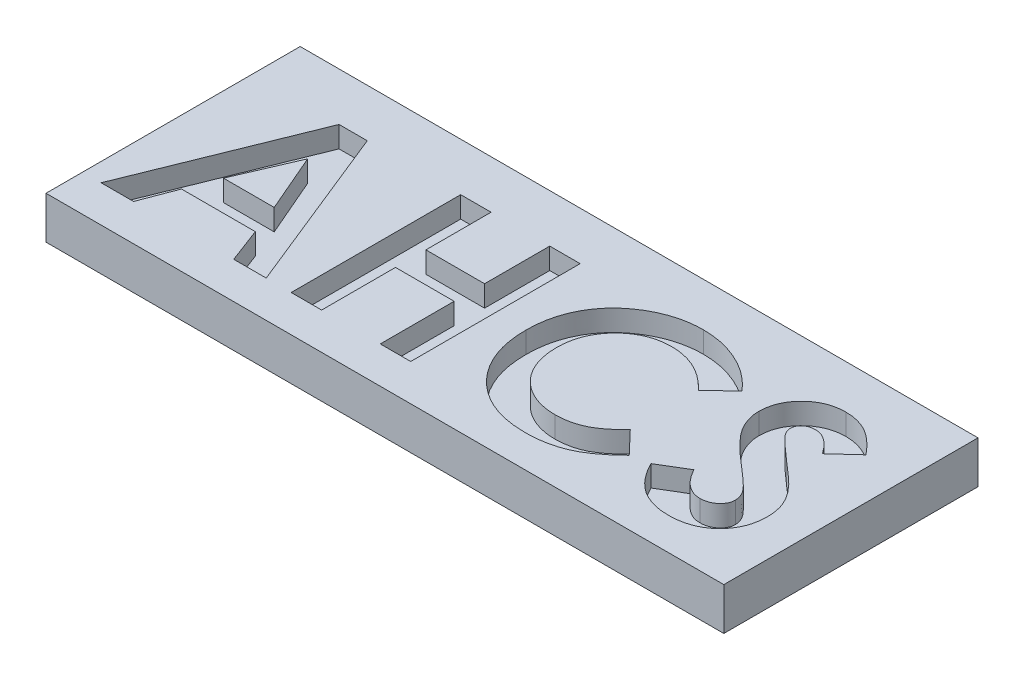
SolidWorks part; units mm, degrees
ref_plane "Front Plane" through (0, 0, 0) normal (0, 0, 1) x (1, 0, 0)
ref_plane "Top Plane" through (0, 0, 0) normal (0, 1, 0) x (1, 0, 0)
ref_plane "Right Plane" through (0, 0, 0) normal (1, 0, 0) x (0, 0, -1)
sketch "Sketch1" plane through (0, 0, 0) normal (0, 1, 0) x (1, 0, 0)
  line L1 (-25.4, -9.525) -> (25.4, -9.525)
  line L2 (-25.4, -9.525) -> (-25.4, 9.525)
  line L3 (-25.4, 9.525) -> (25.4, 9.525)
  line L4 (25.4, -9.525) -> (25.4, 9.525)
  line L5 (-25.4, -9.525) -> (25.4, 9.525) construction
  line L6 (-25.4, 9.525) -> (25.4, -9.525) construction
  point P0 (0, 0)
  dimension "D1" = 50.8
  dimension "D2" = 19.05
extrude "Boss-Extrude1" add sketch "Sketch1" along normal blind 3.175
sketch "Sketch2" plane through (0, 3.175, 0) normal (0, 1, 0) x (1, 0, 0)
  line L0 (-25.4, -6.778) -> (25.4, -6.778) construction
  line L1 (-25.4, 9.525) -> (-25.4, -9.525) construction
  line L2 (25.4, -9.525) -> (25.4, 9.525) construction
  text T0 "<b>AHCS</b>" font "Century Gothic" height in points 48
extrude "Cut-Extrude1" cut sketch "Sketch2" against normal blind 1.5875
